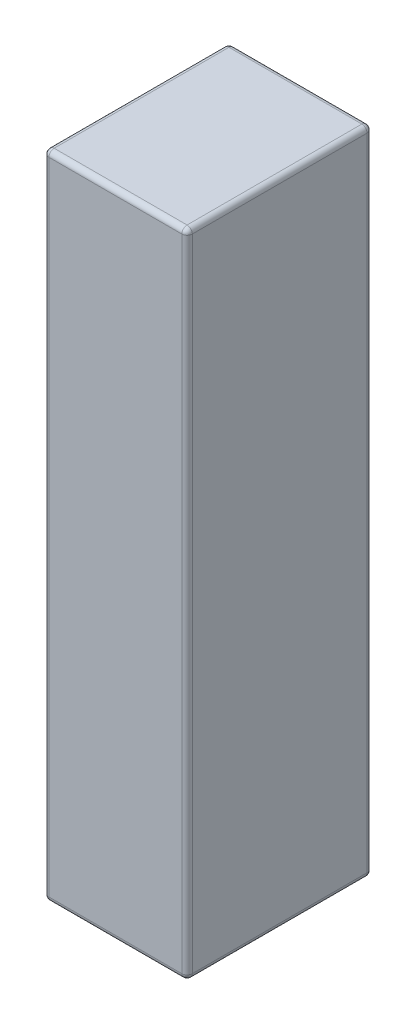
SolidWorks part; units mm, degrees
ref_plane "Front Plane" through (0, 0, 0) normal (0, 0, 1) x (1, 0, 0)
ref_plane "Top Plane" through (0, 0, 0) normal (0, 1, 0) x (1, 0, 0)
ref_plane "Right Plane" through (0, 0, 0) normal (1, 0, 0) x (0, 0, -1)
sketch "Sketch1" plane through (0, 0, 0) normal (0, 1, 0) x (1, 0, 0)
  line L1 (0, 0) -> (13.7, 0)
  line L2 (0, 0) -> (0, 17.7)
  line L3 (0, 17.7) -> (13.7, 17.7)
  line L4 (13.7, 0) -> (13.7, 17.7)
  dimension "D1" = 17.7
  dimension "D2" = 13.7
extrude "Boss-Extrude1" add sketch "Sketch1" along normal blind 62.2
fillet "Fillet1" radius 0.5 12 edges at (0, 31.1, 0) (13.7, 31.1, 0) (13.7, 31.1, -17.7) (0, 31.1, -17.7) (6.85, 62.2, -17.7) (13.7, 62.2, -8.85) (6.85, 62.2, 0) (0, 62.2, -8.85) (6.85, 0, -17.7) (13.7, 0, -8.85) (6.85, 0, 0) (0, 0, -8.85)
